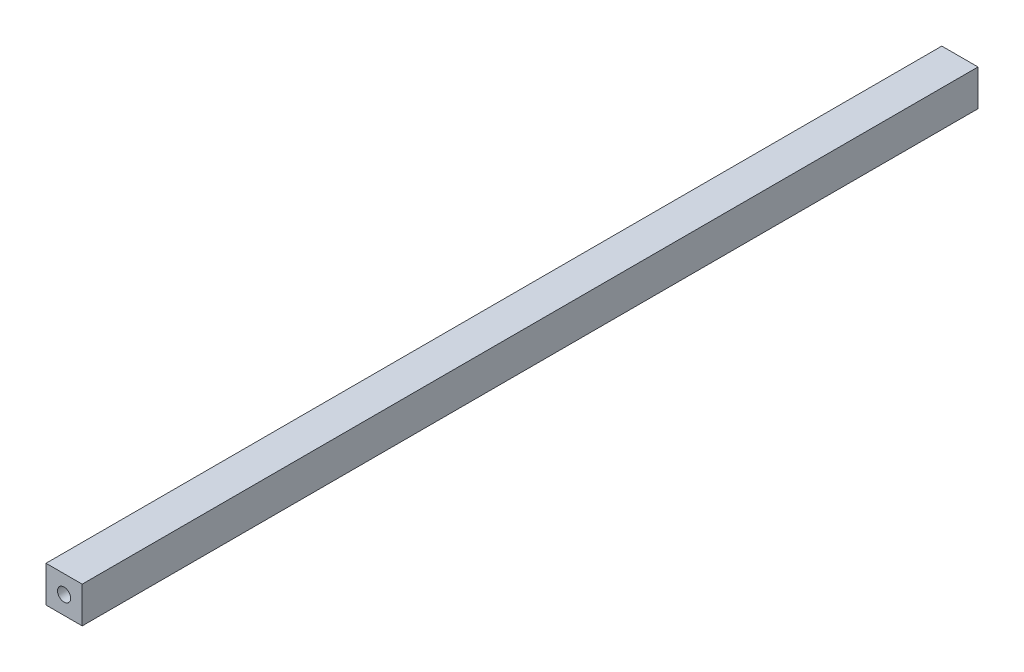
SolidWorks part; units mm, degrees
ref_plane "Front Plane" through (0, 0, 0) normal (0, 0, 1) x (1, 0, 0)
ref_plane "Top Plane" through (0, 0, 0) normal (0, 1, 0) x (1, 0, 0)
ref_plane "Right Plane" through (0, 0, 0) normal (1, 0, 0) x (0, 0, -1)
sketch "Sketch1" plane through (0, 0, 0) normal (0, 0, 1) x (1, 0, 0)
  line L1 (-4, 4) -> (4, 4)
  line L2 (-4, 4) -> (-4, -4)
  line L3 (-4, -4) -> (4, -4)
  line L4 (4, 4) -> (4, -4)
  line L5 (-4, 4) -> (4, -4) construction
  line L6 (-4, -4) -> (4, 4) construction
  point P0 (0, 0)
  dimension "D1" = 8
extrude "Boss-Extrude1" add sketch "Sketch1" along normal mid plane 198
sketch "Sketch2" plane through (0, 0, 99) normal (0, 0, 1) x (1, 0, 0)
  circle A0 centre (0, 0) radius 1.45
  dimension "D1" = 2.9
extrude "Cut-Extrude1" cut sketch "Sketch2" against normal blind 198
